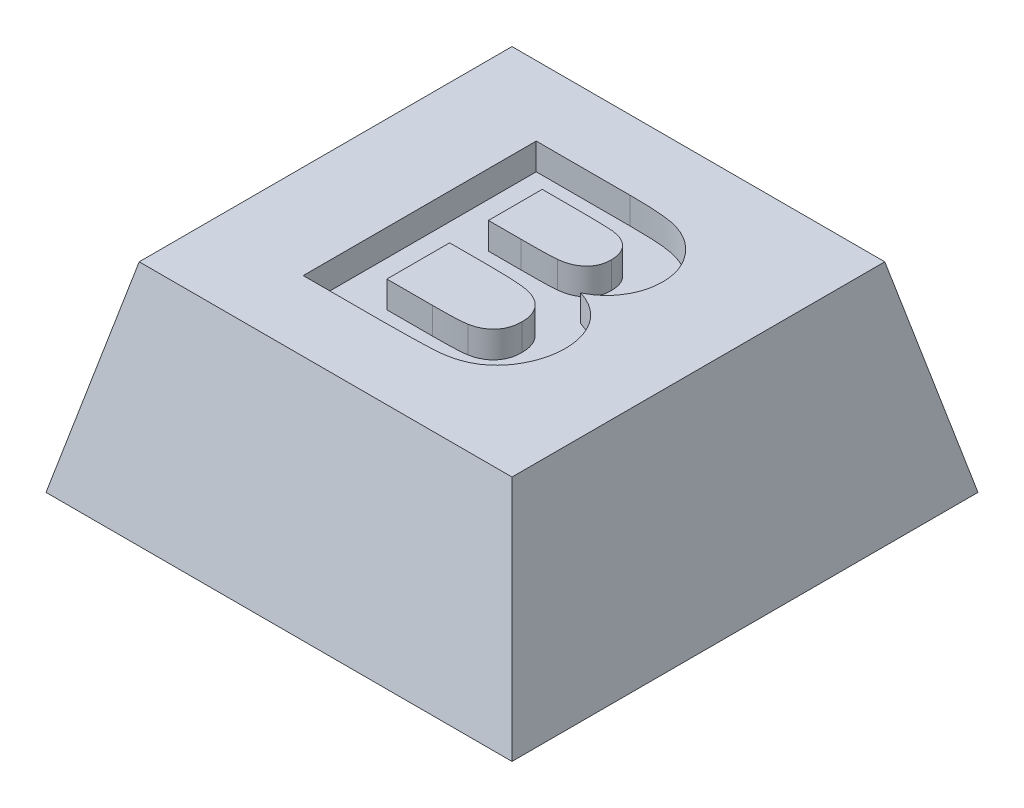
SolidWorks part; units mm, degrees
ref_plane "Front Plane" through (0, 0, 0) normal (0, 0, 1) x (1, 0, 0)
ref_plane "Top Plane" through (0, 0, 0) normal (0, 1, 0) x (1, 0, 0)
ref_plane "Right Plane" through (0, 0, 0) normal (1, 0, 0) x (0, 0, -1)
sketch "Sketch1" plane through (0, 0, 0) normal (0, 1, 0) x (1, 0, 0)
  line L1 (0, 0) -> (7, 0)
  line L2 (0, 0) -> (0, 7)
  line L3 (0, 7) -> (7, 7)
  line L4 (7, 0) -> (7, 7)
  dimension "D1" = 7
  dimension "D2" = 7
extrude "Boss-Extrude1" add sketch "Sketch1" along normal blind 3
sketch "Sketch2" plane through (0, 0, 0) normal (0, 0, 1) x (1, 0, 0)
  line L0 (0, 0) -> (0.7, 3)
  line L1 (0, 3) -> (7, 3) construction
  line L2 (0.7, 3) -> (0, 3)
  line L3 (0, 3) -> (0, 0)
  line L4 (7, 0) -> (6.3, 3)
  line L5 (6.3, 3) -> (7, 3)
  line L6 (7, 3) -> (7, 0)
  dimension "D1" = 0.7
  dimension "D2" = 0.7
extrude "Cut-Extrude1" cut sketch "Sketch2" against normal blind 7
sketch "Sketch3" plane through (0, 0, 0) normal (1, 0, 0) x (0, 0, -1)
  line L0 (0, 0) -> (0.7, 3)
  line L1 (7, 3) -> (0, 3) construction
  line L2 (0.7, 3) -> (0, 3)
  line L3 (0, 3) -> (0, 0)
  line L4 (7, 3) -> (6.3, 3)
  line L5 (6.3, 3) -> (7, 0)
  line L6 (7, 3) -> (7, 0)
  dimension "D1" = 0.7
  dimension "D2" = 0.7
extrude "Cut-Extrude2" cut sketch "Sketch3" along normal blind 11
sketch "Sketch4" plane through (0, 0, 0) normal (0, -1, 0) x (1, 0, 0)
  line L0 (3.5, 0) -> (3.5, -7) construction
  line L1 (0, 0) -> (7, 0) construction
  line L2 (7, -7) -> (0, -7) construction
  line L3 (0, -3.5) -> (7, -3.5) construction
  line L4 (0, -7) -> (0, 0) construction
  line L5 (7, 0) -> (7, -7) construction
  circle A0 centre (3.5, -3.5) radius 1.8
  dimension "D1" = 3.6
extrude "Cut-Extrude3" cut sketch "Sketch4" against normal blind 0.8
sketch "Sketch5" plane through (0, 3, 0) normal (0, 1, 0) x (1, 0, 0)
  text T0 "B" font "Arial" height 3.5
extrude "Cut-Extrude4" cut sketch "Sketch5" against normal blind 0.4
